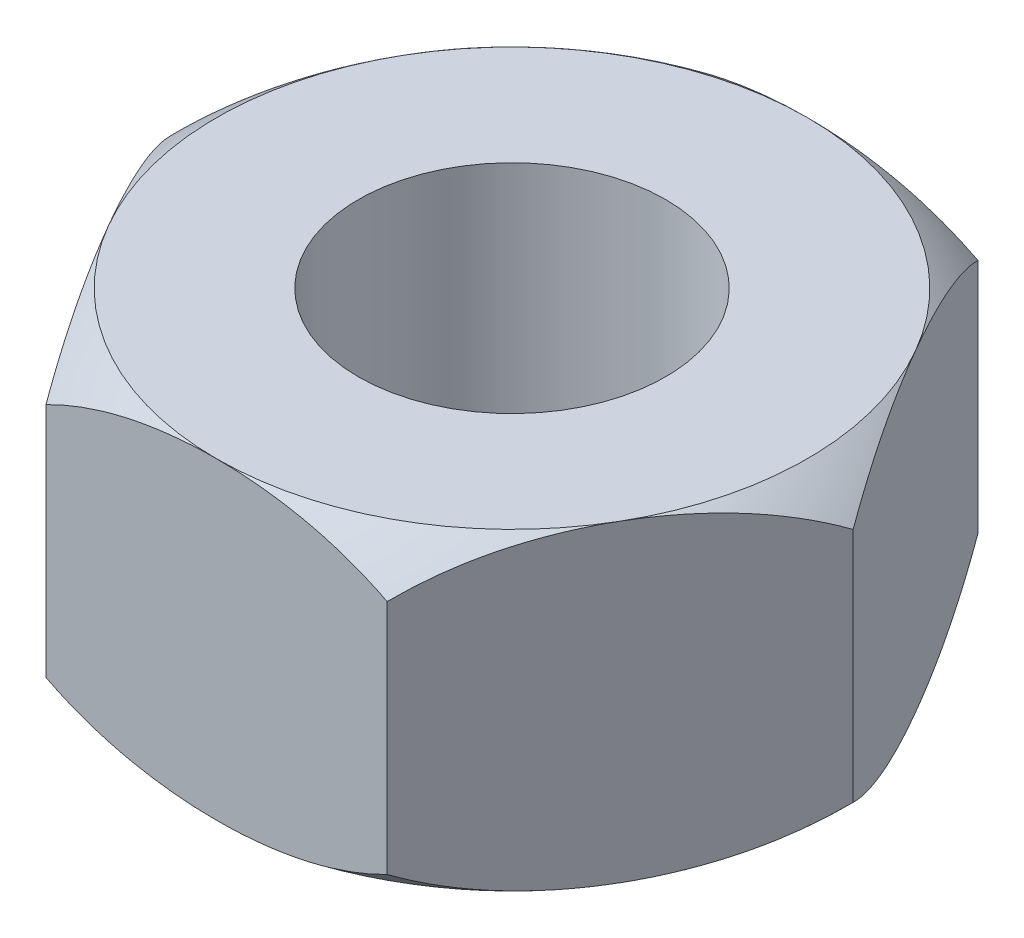
SolidWorks part; units mm, degrees
ref_plane "Front"
ref_plane "Top" through (0, 0, 0) normal (0, 1, 0) x (1, 0, 0)
ref_plane "Right" through (0, 0, 0) normal (1, 0, 0) x (0, 0, -1)
sketch "Sketch1" plane through (0, 0, 0) normal (0, 1, 0) x (1, 0, 0)
  line L1 (7.3323, 0) -> (3.6662, 6.35)
  line L2 (3.6662, 6.35) -> (-3.6662, 6.35)
  line L3 (-3.6662, 6.35) -> (-7.3323, 0)
  line L4 (-7.3323, 0) -> (-3.6662, -6.35)
  line L5 (-3.6662, -6.35) -> (3.6662, -6.35)
  line L6 (3.6662, -6.35) -> (7.3323, 0)
  circle A0 centre (0, 0) radius 6.35 construction
  circle A1 centre (0, 0) radius 3.302
  dimension "D1" = 6.604
  dimension "D2" = 12.7
extrude "Extrude1" add sketch "Sketch1" along normal blind 6.731
sketch "Sketch2" plane through (0, 0, 0) normal (0, 0, 1) x (1, 0, 0)
  line L0 (6.35, 6.731) -> (7.3323, 6.731)
  line L1 (7.3323, 6.731) -> (7.3323, 5.9055)
  line L2 (3.6662, 6.731) -> (7.3323, 6.731) construction
  line L3 (7.3323, 3.3655) -> (-0.0036, 3.3655) construction
  line L4 (7.3323, 6.731) -> (7.3323, 0) construction
  line L5 (7.3323, 0) -> (7.3323, 0.8255)
  line L6 (6.35, 0) -> (7.3323, 0)
  line L7 (0, 0) -> (0, 5.3945) construction
  arc A0 (7.3323, 5.9055) -> (6.35, 6.731) centre (2.7769, 1.4817) ccw
  arc A1 (7.3323, 0.8255) -> (6.35, 0) centre (2.7769, 5.2493) cw
  dimension "D3" = 12.7
  dimension "D1" = 6.35
  dimension "D2" = 5.08
revolve "Cut-Revolve1" cut sketch "Sketch2" angle 360 about L7
